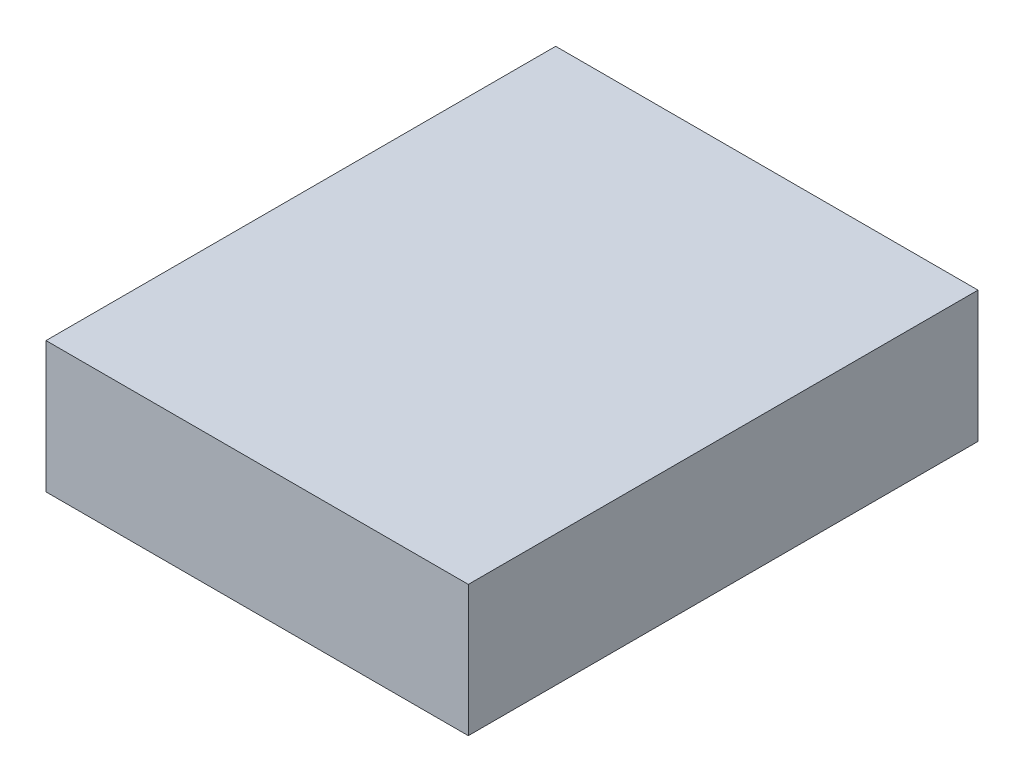
SolidWorks part; units mm, degrees
ref_plane "Спереди" through (0, 0, 0) normal (0, 0, 1) x (1, 0, 0)
ref_plane "Сверху" through (0, 0, 0) normal (0, 1, 0) x (1, 0, 0)
ref_plane "Справа" through (0, 0, 0) normal (1, 0, 0) x (0, 0, -1)
sketch "Эскиз1" plane through (0, 0, 0) normal (0, 1, 0) x (1, 0, 0)
  line L1 (-29, 35) -> (29, 35)
  line L2 (-29, 35) -> (-29, -35)
  line L3 (-29, -35) -> (29, -35)
  line L4 (29, 35) -> (29, -35)
  line L5 (-29, 35) -> (29, -35) construction
  line L6 (-29, -35) -> (29, 35) construction
  point P0 (0, 0)
  dimension "D1" = 58
  dimension "D2" = 70
extrude "Бобышка-Вытянуть1" add sketch "Эскиз1" along normal blind 18
